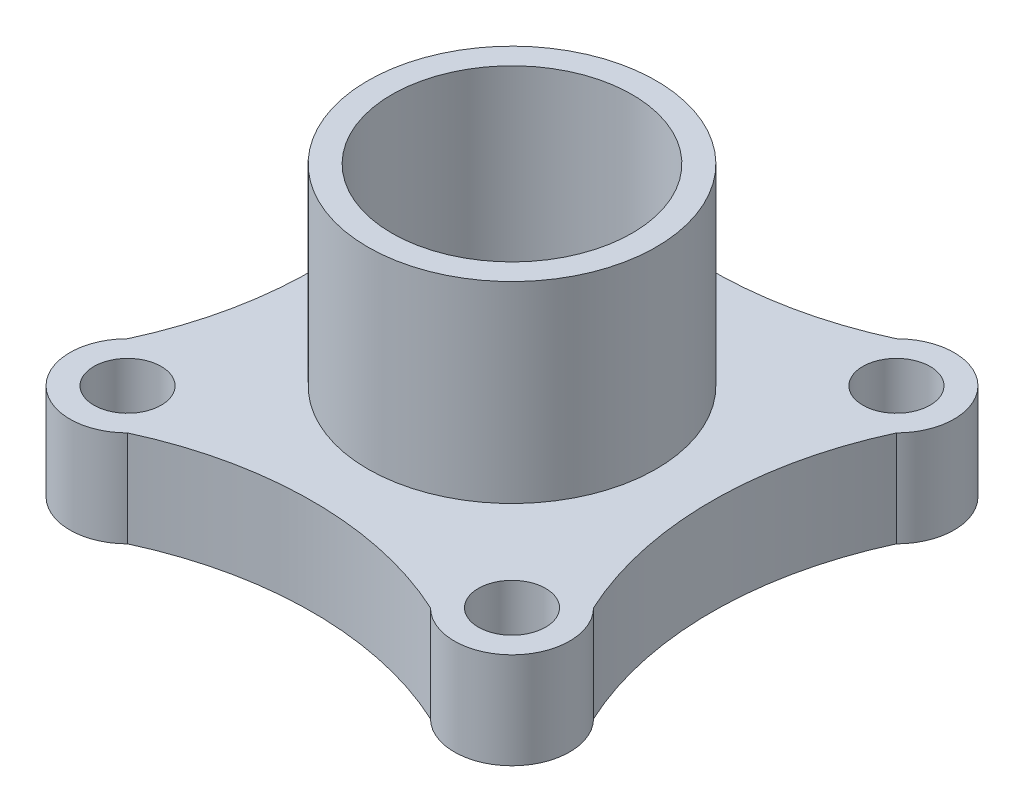
SolidWorks part; units mm, degrees
ref_plane "Front Plane" through (0, 0, 0) normal (0, 0, 1) x (1, 0, 0)
ref_plane "Top Plane" through (0, 0, 0) normal (0, 1, 0) x (1, 0, 0)
ref_plane "Right Plane" through (0, 0, 0) normal (1, 0, 0) x (0, 0, -1)
sketch "Sketch1" plane through (0, 0, 0) normal (0, 1, 0) x (1, 0, 0)
  circle A0 centre (0, 0) radius 30
  dimension "D1" = 60
extrude "Boss-Extrude1" add sketch "Sketch1" along normal blind 40
sketch "Sketch3" plane through (0, 0, 0) normal (0, -1, 0) x (1, 0, 0)
  arc A0 (-48.4853, -31.5147) -> (-31.5147, -48.4853) centre (-40, -40) ccw
  arc A1 (31.5147, -48.4853) -> (48.4853, -31.5147) centre (40, -40) ccw
  arc A2 (-31.5147, 48.4853) -> (-48.4853, 31.5147) centre (-40, 40) ccw
  arc A3 (48.4853, 31.5147) -> (31.5147, 48.4853) centre (40, 40) ccw
  arc A4 (31.5147, 48.4853) -> (-31.5147, 48.4853) centre (0, 116.5428) cw
  arc A5 (48.4853, -31.5147) -> (48.4853, 31.5147) centre (116.5428, 0) cw
  arc A6 (31.5147, -48.4853) -> (-31.5147, -48.4853) centre (0, -116.5428) ccw
  arc A7 (-48.4853, 31.5147) -> (-48.4853, -31.5147) centre (-116.5428, 0) cw
  dimension "D3" = 24
  dimension "D4" = 24
  dimension "D5" = 40
  dimension "D6" = 24
  dimension "D7" = 40
  dimension "D8" = 24
  dimension "D9" = 75
  dimension "D11" = 40
  dimension "D12" = 40
  dimension "D13" = 40
  dimension "D14" = 75
  dimension "D17" = 75
  dimension "D20" = 75
  dimension "D1" = 40
  dimension "D2" = 40
  dimension "D10" = 40
extrude "Boss-Extrude2" add sketch "Sketch3" along normal blind 20
sketch "Sketch4" plane through (0, 0, 0) normal (0, 1, 0) x (1, 0, 0)
  circle A0 centre (-40, 40) radius 7
  circle A1 centre (40, -40) radius 7
  circle A2 centre (40, 40) radius 7
  circle A3 centre (-40, -40) radius 7
  dimension "D1" = 14
  dimension "D2" = 14
  dimension "D5" = 40
  dimension "D6" = 40
  dimension "D7" = 14
  dimension "D8" = 14
  dimension "D3" = 40
  dimension "D4" = 40
extrude "Cut-Extrude2" cut sketch "Sketch4" against normal through all
sketch "Sketch2" plane through (0, 40, 0) normal (0, 1, 0) x (1, 0, 0)
  circle A0 centre (0, 0) radius 25
  dimension "D1" = 50
extrude "Cut-Extrude1" cut sketch "Sketch2" against normal through all
